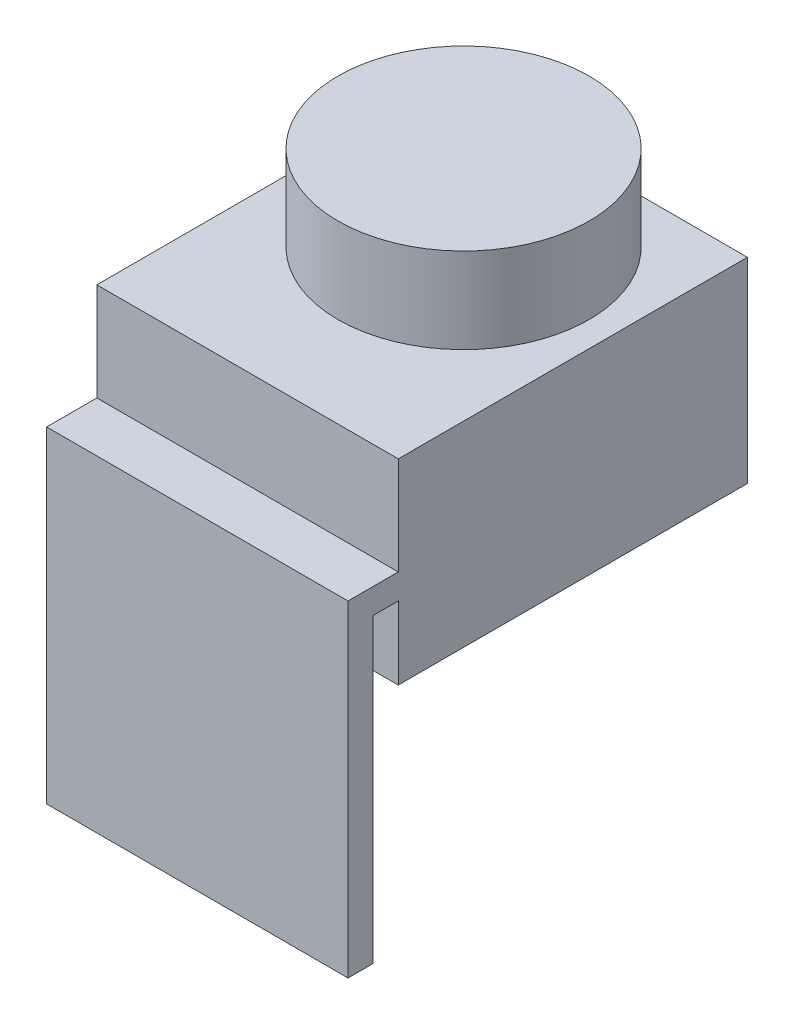
SolidWorks part; units mm, degrees
ref_plane "Front Plane" through (0, 0, 0) normal (0, 0, 1) x (1, 0, 0)
ref_plane "Top Plane" through (0, 0, 0) normal (0, 1, 0) x (1, 0, 0)
ref_plane "Right Plane" through (0, 0, 0) normal (1, 0, 0) x (0, 0, -1)
sketch "Sketch1" plane through (0, 0, 0) normal (0, 1, 0) x (1, 0, 0)
  line L1 (-3, 2.65) -> (3, 2.65)
  line L2 (-3, 2.65) -> (-3, -4.3)
  line L3 (-3, -4.3) -> (3, -4.3)
  line L4 (3, 2.65) -> (3, -4.3)
  dimension "D1" = 6
  dimension "D2" = 3
  dimension "D3" = 6.95
  dimension "D4" = 2.65
extrude "Boss-Extrude1" add sketch "Sketch1" along normal mid plane 3.9
sketch "Sketch2" plane through (0, 1.95, 0) normal (0, 1, 0) x (1, 0, 0)
  circle A0 centre (0, 0) radius 2.5
  dimension "D1" = 5
extrude "Boss-Extrude2" add sketch "Sketch2" along normal blind 1.7
sketch "Sketch3" plane through (0, 0, 4.3) normal (0, 0, 1) x (1, 0, 0)
  line L0 (-3, 1.95) -> (-3, -1.95) construction
  line L1 (-3, 0) -> (3, 0)
  line L2 (-3, 0) -> (-3, -0.5)
  line L3 (-3, -0.5) -> (3, -0.5)
  line L4 (3, 0) -> (3, -0.5)
  line L5 (3, 1.95) -> (3, -1.95) construction
  dimension "D1" = 0.5
  dimension "D2" = 0
  dimension "D3" = 0
  dimension "D4" = 0
extrude "Boss-Extrude3" add sketch "Sketch3" along normal blind 1
sketch "Sketch4" plane through (0, -0.5, 0) normal (0, -1, 0) x (1, 0, 0)
  line L0 (3, 5.3) -> (3, 4.3) construction
  line L1 (-3, 5.3) -> (3, 5.3)
  line L2 (-3, 5.3) -> (-3, 4.8)
  line L3 (-3, 4.8) -> (3, 4.8)
  line L4 (3, 5.3) -> (3, 4.8)
  dimension "D1" = 0.5
extrude "Boss-Extrude4" add sketch "Sketch4" along normal blind 6
equation "\"D2@Sketch1\"=\"D1@Sketch1\"/2"
equation "\"D4@Sketch1\"=5.3/2"
